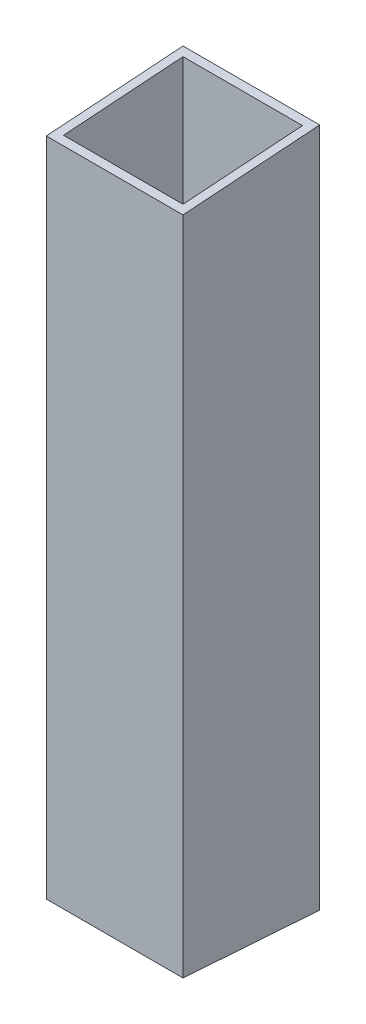
SolidWorks part; units mm, degrees
ref_plane "Front Plane" through (0, 0, 0) normal (0, 0, 1) x (1, 0, 0)
ref_plane "Top Plane" through (0, 0, 0) normal (0, 1, 0) x (1, 0, 0)
ref_plane "Right Plane" through (0, 0, 0) normal (1, 0, 0) x (0, 0, -1)
sketch "Sketch1" plane through (0, 0, 0) normal (0, 1, 0) x (1, 0, 0)
  line L1 (-9.525, -9.525) -> (9.525, -9.525)
  line L2 (-9.525, -9.525) -> (-9.525, 9.525)
  line L3 (-9.525, 9.525) -> (9.525, 9.525)
  line L4 (9.525, -9.525) -> (9.525, 9.525)
  line L5 (-9.525, -9.525) -> (9.525, 9.525) construction
  line L6 (-9.525, 9.525) -> (9.525, -9.525) construction
  point P0 (0, 0)
  dimension "D1" = 19.05
extrude "Boss-Extrude1" add sketch "Sketch1" along normal blind 92.1
ref_plane "Plane1" through (0, 46.05, 0) normal (0, 1, 0) x (1, 0, 0)
sketch "Sketch2" plane through (9.525, 0, 0) normal (1, 0, 0) x (0, 0, -1)
  line L0 (-9.525, 92.1) -> (9.525, 92.1)
  line L1 (9.525, 92.1) -> (9.525, 93.4321)
  line L2 (9.525, 93.4321) -> (-9.525, 92.1)
  line L3 (12.385, 46.05) -> (-12.385, 46.05) construction
  line L4 (9.525, -1.3321) -> (-9.525, 0)
  line L5 (9.525, 0) -> (9.525, -1.3321)
  line L6 (-9.525, 0) -> (9.525, 0)
  dimension "D1" = 4
extrude "Boss-Extrude2" add sketch "Sketch2" against normal blind 19.05
sketch "Sketch4" plane through (0, 0, 0) normal (0, 1, 0) x (1, 0, 0)
  line L8 (8.325, -8.325) -> (8.325, 8.325)
  line L9 (8.325, 8.325) -> (-8.325, 8.325)
  line L10 (-8.325, 8.325) -> (-8.325, -8.325)
  line L11 (-8.325, -8.325) -> (8.325, -8.325)
  line L12 (8.325, -8.325) -> (8.325, 8.325)
  line L13 (8.325, 8.325) -> (-8.325, 8.325)
  line L14 (-8.325, 8.325) -> (-8.325, -8.325)
  line L15 (-8.325, -8.325) -> (8.325, -8.325)
  dimension "D1" = 1.2
extrude "Cut-Extrude1" cut sketch "Sketch4" against normal through all both and the other way through all
